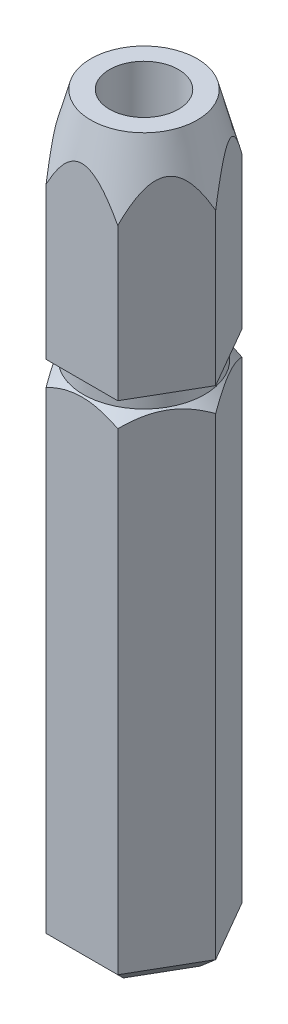
SolidWorks part; units mm, degrees
material "6061 Alloy"
ref_plane "front" through (0, 0, 0) normal (0, 0, 1) x (1, 0, 0)
ref_plane "top" through (0, 0, 0) normal (0, 1, 0) x (1, 0, 0)
ref_plane "right" through (0, 0, 0) normal (1, 0, 0) x (0, 0, -1)
sketch "Sketch1" plane through (0, 0, 0) normal (0, 1, 0) x (1, 0, 0)
  line L1 (4.1244, -7.1437) -> (8.2489, 0)
  line L2 (8.2489, 0) -> (4.1244, 7.1437)
  line L3 (4.1244, 7.1437) -> (-4.1244, 7.1437)
  line L4 (-4.1244, 7.1437) -> (-8.2489, 0)
  line L5 (-8.2489, 0) -> (-4.1244, -7.1437)
  line L6 (-4.1244, -7.1437) -> (4.1244, -7.1437)
  circle A0 centre (0, 0) radius 7.1437 construction
  dimension "D1" = 14.2875
extrude "Extrude1" add sketch "Sketch1" along normal blind 84.1375
sketch "Sketch4" plane through (0, 84.1375, 0) normal (0, 1, 0) x (-1, 0, 0)
  circle A0 centre (0, 0) radius 3.9688
  dimension "D1" = 7.9375
extrude "Cut-Extrude1" cut sketch "Sketch4" against normal through all
ref_plane "Plane1" through (0, 0, 0) normal (0.866, 0, -0.5) x (-0.5, 0, -0.866)
sketch "Sketch2" plane through (0, 0, 0) normal (0.866, 0, -0.5) x (-0.5, 0, -0.866)
  line L0 (0, -6.2883) -> (0, 88.0375) construction
  line L2 (8.2489, 84.1375) -> (8.2489, 76.2)
  line L4 (8.2489, 84.1375) -> (6.122, 84.1375)
  line L5 (6.122, 84.1375) -> (8.2489, 76.2)
  line L6 (-4.1244, 84.1375) -> (4.1244, 84.1375) construction
  line L7 (8.2489, 84.1375) -> (8.2489, 0) construction
  dimension "D1" = 15
  dimension "D2" = 7.9375
revolve "Cut-Revolve1" cut sketch "Sketch2" angle 360 about L0
sketch "Sketch3" plane through (0, 0, 0) normal (0.866, 0, -0.5) x (-0.5, 0, -0.866)
  line L0 (0, -5.5728) -> (0, 98.8641) construction
  line L2 (8.2489, 55.9496) -> (6.985, 57.2135)
  line L3 (8.2489, 55.9496) -> (8.2489, 58.7375)
  line L4 (8.2489, 58.7375) -> (6.985, 58.7375)
  line L5 (6.985, 57.2135) -> (6.985, 58.7375)
  line L6 (6.122, 84.1375) -> (-6.122, 84.1375) construction
  line L7 (8.2489, 76.2) -> (8.2489, 0) construction
  dimension "D1" = 25.4
  dimension "D2" = 13.97
  dimension "D3" = 45
  dimension "D4" = 1.524
revolve "Cut-Revolve2" cut sketch "Sketch3" angle 360 about L0
chamfer "Chamfer1" distance 1.524 angle 45 7 edges at (6.1867, 0, 3.5719) (6.1867, 0, -3.5719) (0, 0, -7.1437) (-6.1867, 0, -3.5719) (-6.1867, 0, 3.5719) (0, 0, 7.1437) (0, 0, 3.9688)
sketch "Text Alginment" plane through (0, 0, 7.1437) normal (0, 0, 1) x (1, 0, 0)
  line L0 (1.905, 1.524) -> (1.905, 56.8051) construction
  line L1 (-4.1244, 1.524) -> (4.1244, 1.524) construction
  spline S0 degree 3 poles (4.1244, 55.9496) (3.8054, 56.1091) (3.4802, 56.258) (2.8132, 56.5269) (2.4696, 56.6472) (1.4328, 56.9427) (0.727, 57.0546) (-0.3607, 57.0548) (-0.722, 57.0269) (-1.4298, 56.9215) (-1.7784, 56.8441) (-2.467, 56.648) (-2.8078, 56.5289) (-3.4782, 56.2589) (-3.8046, 56.1096) (-4.1244, 55.9496) knots 0 0 0 0 0.125 0.125 0.25 0.25 0.5 0.5 0.625 0.625 0.75 0.75 0.875 0.875 1 1 1 1 construction
  dimension "D1" = 1.905
sketch "Sketch6" plane through (0, 0, 7.1437) normal (0, 0, 1) x (1, 0, 0)
  text T0 "PIN  1"
extrude "PIN 1" [suppressed] cut sketch "Sketch6" against normal blind 0.0254
sketch "Sketch7" plane through (0, 0, 7.1437) normal (0, 0, 1) x (1, 0, 0)
  text T0 "PIN  2"
extrude "PIN 2" [suppressed] cut sketch "Sketch7" against normal blind 0.0254
sketch "Sketch8" plane through (0, 0, 7.1437) normal (0, 0, 1) x (1, 0, 0)
  text T0 "PIN  A"
extrude "PIN A" [suppressed] cut sketch "Sketch8" against normal blind 0.0254
sketch "Sketch9" plane through (0, 0, 7.1437) normal (0, 0, 1) x (1, 0, 0)
  text T0 "PIN  B"
extrude "PIN B" [suppressed] cut sketch "Sketch9" against normal blind 0.0254
